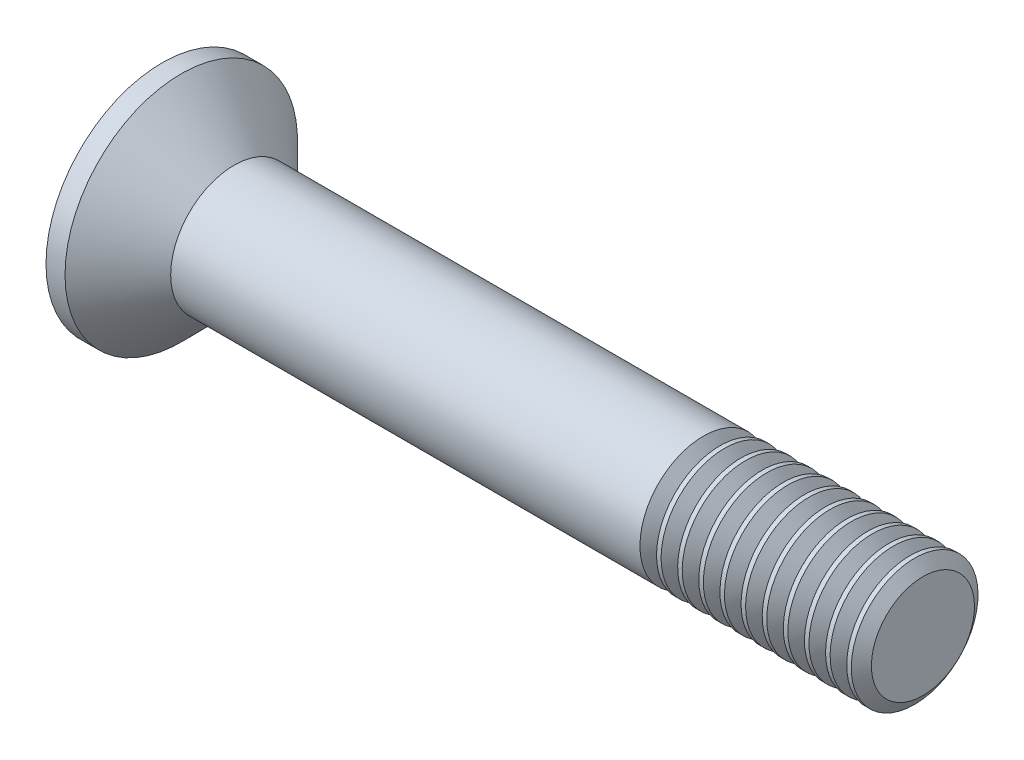
SolidWorks part; units mm, degrees
revolve "Base-Revolve" add sketch "BodySke" angle 360 about L5
sketch "BodySke" plane through (0, 0, 0) normal (0, 0, 1) x (1, 0, 0)
  line L0 (0, 0) -> (0, 2.75)
  line L1 (0, 2.75) -> (0.45, 2.75)
  line L2 (1.7, 1.5) -> (18, 1.5)
  line L3 (18, 1.5) -> (18, 0)
  line L4 (18, 0) -> (0, 0)
  line L5 (-6.35, 0) -> (82.55, 0) construction
  line L6 (1.7, -1.5) -> (18, -1.5) construction
  line L7 (0.45, -2.75) -> (1.7, -1.5) construction
  line L8 (0.45, 2.75) -> (1.7, 1.5)
  line L9 (0, -2.75) -> (0.45, -2.75) construction
  line L10 (2.2, 3.0875) -> (2.2, -6.4375) construction
  line L11 (13, 6.35) -> (13, -3.175) construction
  dimension "Diameter" = 3
  dimension "Length" = 18
  dimension "Head_ht" = 1.7
  dimension "Head_dia" = 5.5
  dimension "Head_ang" = 90
  dimension "D6" = 0.45
  dimension "Advance" = 0.5
  dimension "Thread_nom" = 5
cosmetic thread "ThreadCosmetic" [suppressed] parameters "Thread_length"=5, "Thread_minor"=2.439
extrude "Slot" [suppressed] cut sketch "Sketch2" against normal blind 0.9
sketch "Sketch2" plane through (0, 0, 0) normal (-1, 0, 0) x (0, 0, 1)
  line L0 (-2.75, -0.5) -> (2.75, -0.5)
  line L1 (-2.75, -0.5) -> (-2.75, 0.5)
  line L2 (2.75, 0.5) -> (-2.75, 0.5)
  line L3 (2.75, 0.5) -> (2.75, -0.5)
  dimension "Slot_width" = 1
  dimension "D1" = 0.5
  dimension "D2" = 5.5
  dimension "D3" = 2.75
ref_plane "Plane1" through (0, 0, 0) normal (0, 0, 1) x (1, 0, 0)
ref_plane "Plane2" through (0, 0, 0) normal (0, 1, 0) x (1, 0, 0)
ref_plane "Plane3" through (0, 0, 0) normal (1, 0, 0) x (0, 0, -1)
sketch "Sketch3" plane through (0, 0, 0) normal (-1, 0, 0) x (0, 0, 1)
  line L0 (-0.395, 1.55) -> (0.395, 1.55)
  line L1 (0.395, 1.55) -> (0.395, -1.55)
  line L2 (0.395, -1.55) -> (-0.395, -1.55)
  line L3 (-0.395, -1.55) -> (-0.395, 1.55)
  dimension "Cross_dia" = 3.1
  dimension "Cross_width" = 0.79
  dimension "D1" = 1.55
  dimension "D2" = 0.395
ref_plane "Plane4" through (2.08, 0, 0) normal (-1, 0, 0) x (0, 0, 1)
sketch "Sketch4" plane through (2.08, 0, 0) normal (-1, 0, 0) x (0, 0, 1)
  line L0 (-0.1975, 0.1975) -> (0.1975, 0.1975)
  line L3 (0.1975, 0.1975) -> (0.1975, -0.1975)
  line L4 (0.1975, -0.1975) -> (-0.1975, -0.1975)
  line L5 (-0.1975, -0.1975) -> (-0.1975, 0.1975)
  dimension "D2" = 0.395
  dimension "D1" = 0.395
  dimension "D3" = 0.1975
  dimension "D4" = 0.1975
loft "Cross" cut profiles "Sketch3", "Sketch4"
pattern_circular "CirPattern1" count 2 every 90 about axis through (0, 0, 0) along (1, 0, 0) of "Cross"
sketch "ThdSchSke" plane through (0, 0, 0) normal (0, 0, 1) x (1, 0, 0)
  line L0 (13, -1.2195) -> (12.8036, -1.5)
  line L1 (13, -1.2195) -> (13.1964, -1.5)
  line L2 (13.1964, -1.5) -> (13.1964, -1.875)
  line L3 (-3.175, 0) -> (5.1513, 0) construction
  line L5 (13.1964, -1.875) -> (12.8036, -1.875)
  line L6 (12.8036, -1.875) -> (12.8036, -1.5)
  line L7 (0, 2.75) -> (0, -2.75) construction
  dimension "Diameter" = 3
  dimension "Thread_minor" = 2.439
  dimension "Start" = 13
revolve "ThreadSchematic" cut sketch "ThdSchSke" angle 360 about L3
pattern_linear "ThdSchPat" count 11 spacing 0.5 along (1, 0, 0) of "ThreadSchematic"
equation "\"D1@Sketch3\" = \"Cross_dia@Sketch3\" / 2"
equation "\"D2@Sketch3\" = \"Cross_width@Sketch3\" / 2"
equation "\"D1@Sketch4\" = \"Cross_width@Sketch3\" *.5"
equation "\"D2@Sketch4\" = \"D1@Sketch4\""
equation "\"D4@Sketch4\" = \"D2@Sketch4\" / 2"
equation "\"D3@Sketch4\" = \"D1@Sketch4\" / 2"
equation "\"D1@Sketch2\" = \"Slot_width@Sketch2\" / 2"
equation "\"D2@Sketch2\" = \"Head_dia@BodySke\""
equation "\"D3@Sketch2\" = \"D2@Sketch2\" / 2"
equation "\"Thread_length@ThreadCosmetic\" = ((sgn( (\"Length@BodySke\" - \"Advance@BodySke\" - \"Head_ht@BodySke\" ) - \"Thread_nom@BodySke\" )-1)*( (\"Length@BodySke\" - \"Advance@BodySke\" - \"Head_ht@BodySke\" ) - \"Thread_nom@BodySke\" ))/-2+ \"Thread_nom@BodySke\""
equation "\"Thread_minor@ThdSchSke\" = \"Thread_minor@ThreadCosmetic\""
equation "\"Diameter@ThdSchSke\" = \"Diameter@BodySke\""
equation "\"Overcut@ThdSchSke\" = \"Diameter@BodySke\" * 1.25"
equation "\"Start@ThdSchSke\" = 0.000001 + \"Length@BodySke\" - \"Thread_length@ThreadCosmetic\"  '---Countersunk---"
equation "\"Num_threads@ThdSchPat\" = int( \"Thread_length@ThreadCosmetic\" / \"Advance@BodySke\" + 0.999 )  + 1"
equation "\"Advance@ThdSchPat\" = \"Thread_length@ThreadCosmetic\" /  (\"Num_threads@ThdSchPat\" - 1) 'relax it"
